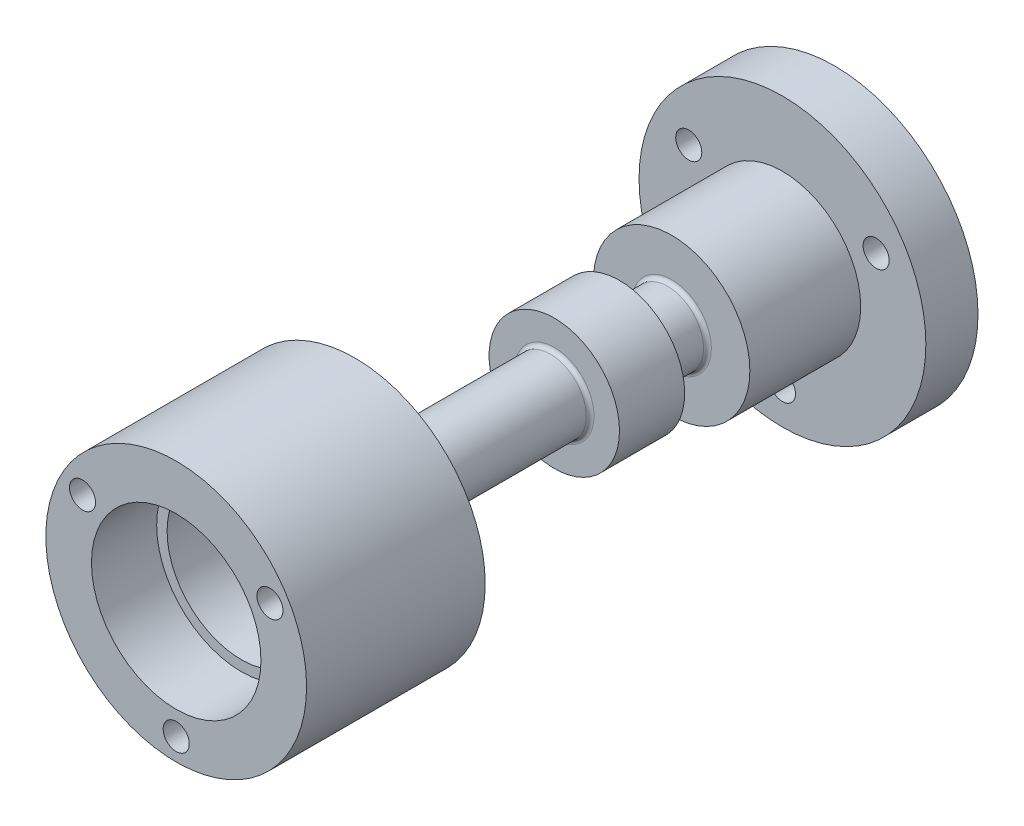
SolidWorks part; units mm, degrees
material "AISI 4340 Steel, normalized"
ref_plane "Front Plane" through (0, 0, 0) normal (0, 0, 1) x (1, 0, 0)
ref_plane "Top Plane" through (0, 0, 0) normal (0, 1, 0) x (1, 0, 0)
ref_plane "Right Plane" through (0, 0, 0) normal (1, 0, 0) x (0, 0, -1)
sketch "Sketch1" plane through (0, 0, 0) normal (0, 0, 1) x (1, 0, 0)
  circle A0 centre (0, 0) radius 11
extrude "Mounting_Flange" add sketch "Sketch1" along normal blind 4 from offset 4
sketch "Sketch2" plane through (0, 0, 0) normal (0, 0, 1) x (1, 0, 0)
  circle A0 centre (0, 0) radius 2.75
extrude "D5p5_Central_Post" add sketch "Sketch2" along normal blind 32.81
sketch "Sketch3" plane through (0, 0, 0) normal (0, 0, 1) x (1, 0, 0)
  circle A0 centre (0, 0) radius 10
extrude "Closed_Floor_Below_Shaft_Nose" add sketch "Sketch3" along normal blind 2.2 from offset 32.8
sketch "Sketch4" plane through (0, 0, 0) normal (0, 0, 1) x (1, 0, 0)
  circle A0 centre (0, 0) radius 10
  circle A1 centre (0, 0) radius 5.7
extrude "Shaft_And_Clip_Clearance" add sketch "Sketch4" along normal blind 6.5 from offset 35
sketch "Sketch5" plane through (0, 0, 0) normal (0, 0, 1) x (1, 0, 0)
  circle A0 centre (0, 0) radius 10
  circle A1 centre (0, 0) radius 6.5
extrude "Lower_686ZZ_Seat" add sketch "Sketch5" along normal blind 5 from offset 41.5
sketch "Sketch6" plane through (0, 0, -4) normal (0, 0, -1) x (-1, 0, 0)
  circle A0 centre (-7.188, 4.15) radius 1
  circle A1 centre (7.188, 4.15) radius 1
  circle A2 centre (0, -8.3) radius 1
extrude "Base_Three_M2_Through_Thread_Major_Envelopes" cut sketch "Sketch6" against normal blind 4.01
sketch "Sketch7" plane through (0, 0, 46.5) normal (0, 0, 1) x (1, 0, 0)
  circle A0 centre (7.188, 4.15) radius 1
  circle A1 centre (-7.188, 4.15) radius 1
  circle A2 centre (0, -8.3) radius 1
extrude "Top_Cap_Three_M2_Blind_Thread_Major_Envelopes" cut sketch "Sketch7" against normal blind 4.3
sketch "Sketch8" plane through (0, 0, 0) normal (0, 0, 1) x (1, 0, 0)
  circle A0 centre (0, 0) radius 6
extrude "Bench_D12_Root_To8p5" add sketch "Sketch8" along normal blind 8.5
sketch "Sketch9" plane through (0, 0, 0) normal (0, 0, 1) x (1, 0, 0)
  circle A0 centre (0, 0) radius 5
extrude "Bench_D10_Mid_Collar_12p5_To17p5" add sketch "Sketch9" along normal blind 5 from offset 12.5
fillet "Bench_Step_Transitions_Fillet_R0p30" radius 0.3 3 edges at (2.75, 0, 17.5) (2.75, 0, 8.5) (2.75, 0, 12.5)
